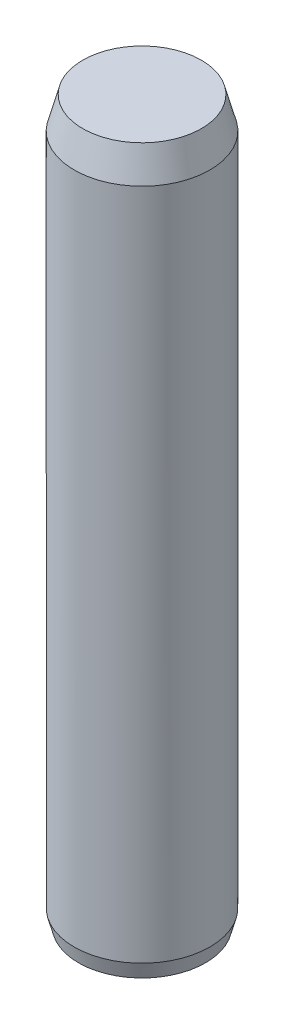
SolidWorks part; units mm, degrees
material "1.7131 (16MnCr5)"
ref_plane "Front Plane" through (0, 0, 0) normal (0, 0, 1) x (1, 0, 0)
ref_plane "Top Plane" through (0, 0, 0) normal (0, 1, 0) x (1, 0, 0)
ref_plane "Right Plane" through (0, 0, 0) normal (1, 0, 0) x (0, 0, -1)
sketch "Sketch1" plane through (0, 0, 0) normal (0, 1, 0) x (1, 0, 0)
  circle A0 centre (0, 0) radius 16
  dimension "D1" = 32
extrude "Boss-Extrude1" add sketch "Sketch1" along normal blind 170
chamfer "Chamfer1" distance 2 angle 75 1 edges at (0, 170, 16)
chamfer "Chamfer2" distance 1 angle 75 1 edges at (0, 0, 16)
